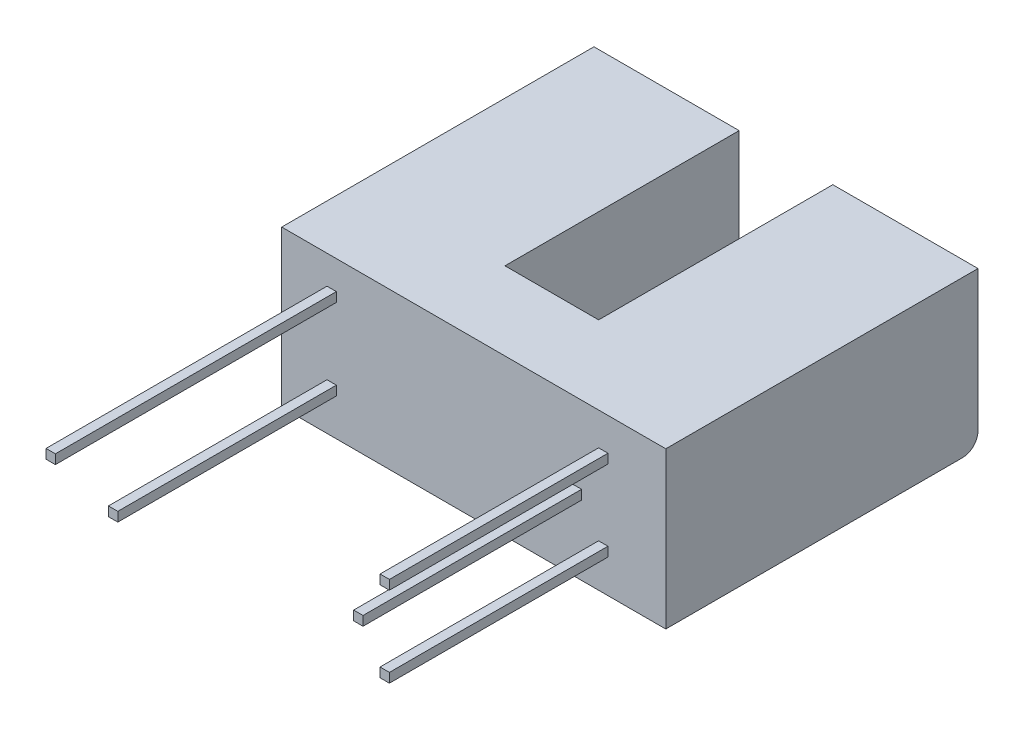
SolidWorks part; units mm, degrees
ref_plane "Front Plane" through (0, 0, 0) normal (0, 0, 1) x (1, 0, 0)
ref_plane "Top Plane" through (0, 0, 0) normal (0, 1, 0) x (1, 0, 0)
ref_plane "Right Plane" through (0, 0, 0) normal (1, 0, 0) x (0, 0, -1)
sketch "Sketch1" plane through (0, 0, 0) normal (0, 1, 0) x (1, 0, 0)
  line L1 (-6.15, 5) -> (6.15, 5)
  line L2 (-6.15, 5) -> (-6.15, -5)
  line L3 (-6.15, -5) -> (6.15, -5)
  line L4 (6.15, 5) -> (6.15, -5)
  line L5 (-6.15, 5) -> (6.15, -5) construction
  line L6 (-6.15, -5) -> (6.15, 5) construction
  point P0 (0, 0)
  dimension "D1" = 10
  dimension "D2" = 12.3
extrude "Boss-Extrude1" add sketch "Sketch1" along normal blind 5
sketch "Sketch2" plane through (0, 5, 0) normal (0, 1, 0) x (1, 0, 0)
  line L0 (0, 0) -> (0, 5) construction
  line L1 (6.15, 5) -> (-6.15, 5) construction
  line L2 (0, 5) -> (0, -5) construction
  line L3 (-6.15, -5) -> (6.15, -5) construction
  line L5 (-1.5, 5) -> (0, 5)
  line L6 (-1.5, 5) -> (-1.5, -2.5)
  line L7 (-1.5, -2.5) -> (0, -2.5)
  line L8 (0, 5) -> (0, -2.5)
  dimension "D1" = 7.5
  dimension "D2" = 1.5
extrude "Cut-Extrude1" cut sketch "Sketch2" against normal blind 5 contours L6 L7 L8 L5
pattern_linear "LPattern1" count 2 spacing 1.5 along (1, 0, 0) of "Cut-Extrude1"
fillet "Fillet4" radius 0.5 2 edges at (-3.825, 0, -5) (3.825, 0, -5)
sketch "Sketch3" plane through (0, 0, 5) normal (0, 0, 1) x (1, 0, 0)
  line L1 (-4.6997, 4.0851) -> (-4.3997, 4.0851)
  line L2 (-4.6997, 4.0851) -> (-4.6997, 3.7851)
  line L3 (-4.6997, 3.7851) -> (-4.3997, 3.7851)
  line L4 (-4.3997, 4.0851) -> (-4.3997, 3.7851)
  dimension "D1" = 0.3
  dimension "D2" = 0.3
extrude "Boss-Extrude2" add sketch "Sketch3" along normal blind 9
sketch "Sketch4" plane through (0, 0, 5) normal (0, 0, 1) x (1, 0, 0)
  line L1 (-4.6997, 1.4903) -> (-4.3997, 1.4903)
  line L2 (-4.6997, 1.4903) -> (-4.6997, 1.1903)
  line L3 (-4.6997, 1.1903) -> (-4.3997, 1.1903)
  line L4 (-4.3997, 1.4903) -> (-4.3997, 1.1903)
  dimension "D1" = 0.3
  dimension "D2" = 0.3
extrude "Boss-Extrude3" add sketch "Sketch4" along normal blind 7 contours L3 L4 L1 L2
sketch "Sketch5" plane through (0, 0, 5) normal (0, 0, 1) x (1, 0, 0)
  line L1 (3.999, 3.9514) -> (4.299, 3.9514)
  line L2 (3.999, 3.9514) -> (3.999, 3.6514)
  line L3 (3.999, 3.6514) -> (4.299, 3.6514)
  line L4 (4.299, 3.9514) -> (4.299, 3.6514)
  dimension "D1" = 0.3
  dimension "D2" = 0.3
extrude "Boss-Extrude4" add sketch "Sketch5" along normal blind 7 contours L3 L4 L1 L2
sketch "Sketch6" plane through (0, 0, 5) normal (0, 0, 1) x (1, 0, 0)
  line L1 (3.999, 1.3721) -> (4.299, 1.3721)
  line L2 (3.999, 1.3721) -> (3.999, 1.0721)
  line L3 (3.999, 1.0721) -> (4.299, 1.0721)
  line L4 (4.299, 1.3721) -> (4.299, 1.0721)
  dimension "D1" = 0.3
  dimension "D2" = 0.3
extrude "Boss-Extrude5" add sketch "Sketch6" along normal blind 7
sketch "Sketch7" plane through (0, 0, 5) normal (0, 0, 1) x (1, 0, 0)
  line L1 (3.1536, 2.5285) -> (3.4536, 2.5285)
  line L2 (3.1536, 2.5285) -> (3.1536, 2.2285)
  line L3 (3.1536, 2.2285) -> (3.4536, 2.2285)
  line L4 (3.4536, 2.5285) -> (3.4536, 2.2285)
  dimension "D1" = 0.3
  dimension "D2" = 0.3
extrude "Boss-Extrude6" add sketch "Sketch7" along normal blind 7
